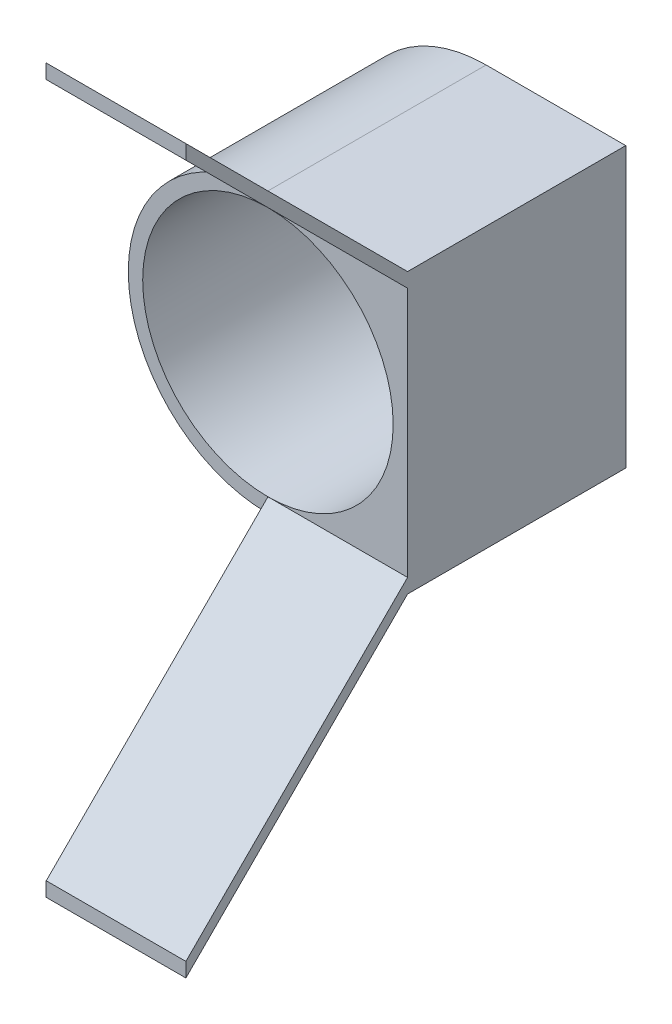
SolidWorks part; units mm, degrees
ref_plane "Front Plane" through (0, 0, 0) normal (0, 0, 1) x (1, 0, 0)
ref_plane "Top Plane" through (0, 0, 0) normal (0, 1, 0) x (1, 0, 0)
ref_plane "Right Plane" through (0, 0, 0) normal (1, 0, 0) x (0, 0, -1)
sketch "Sketch1" plane through (0, 0, 0) normal (0, 0, 1) x (1, 0, 0)
  circle A0 centre (0, 0) radius 14.35
  circle A1 centre (0, 0) radius 16
  dimension "D1" = 28.7
  dimension "D2" = 32
extrude "Boss-Extrude1" add sketch "Sketch1" along normal blind 25
sketch "Sketch3" plane through (0, 0, 0) normal (0, 0, 1) x (1, 0, 0)
  line L0 (0, 16) -> (16, 16)
  line L2 (16, 16) -> (16, -16)
  line L4 (16, -16) -> (0, -16)
  circle A0 centre (0, 0) radius 16 construction
  circle A1 centre (0, 0) radius 16
  point P5 (0, 0)
  point P11 (0, 0)
  point P12 (0, 0)
extrude "Boss-Extrude3" add sketch "Sketch3" along normal up to surface (25 mm away) contours A1 L2 L0 | A1 L4 L2 up to face at (16, 0, 25)
sketch "Sketch2" plane through (0, 0, 0) normal (1, 0, 0) x (0, 0, -1)
  line L0 (-25, -16) -> (-50.4, -41.4)
  line L1 (-25, 14.35) -> (-25, -14.35) construction
  line L2 (-25, 14.35) -> (-25, -14.35)
  line L3 (-25, -14.35) -> (-50.4, -39.75)
  line L4 (-50.4, -39.75) -> (-50.4, -41.4)
  line L5 (-25, -14.35) -> (-25, -16)
  line L6 (17.6, 0) -> (-17.6, 0) construction
  line L7 (-25, 14.35) -> (-25, 16)
  line L8 (-25, 16) -> (-50.4, 41.4)
  line L9 (-50.4, 39.75) -> (-50.4, 41.4)
  line L10 (-25, 14.35) -> (-50.4, 39.75)
  point P5 (-50.4, -40.575)
  point P13 (0, 0)
  dimension "D1" = 45
  dimension "D2" = 25.4
extrude "Boss-Extrude4" add sketch "Sketch2" along normal up to surface (16 mm away) contours L10 L7 L8 L9 | L5 L3 L4 L0 up to face at (16, 0, 12.5)
